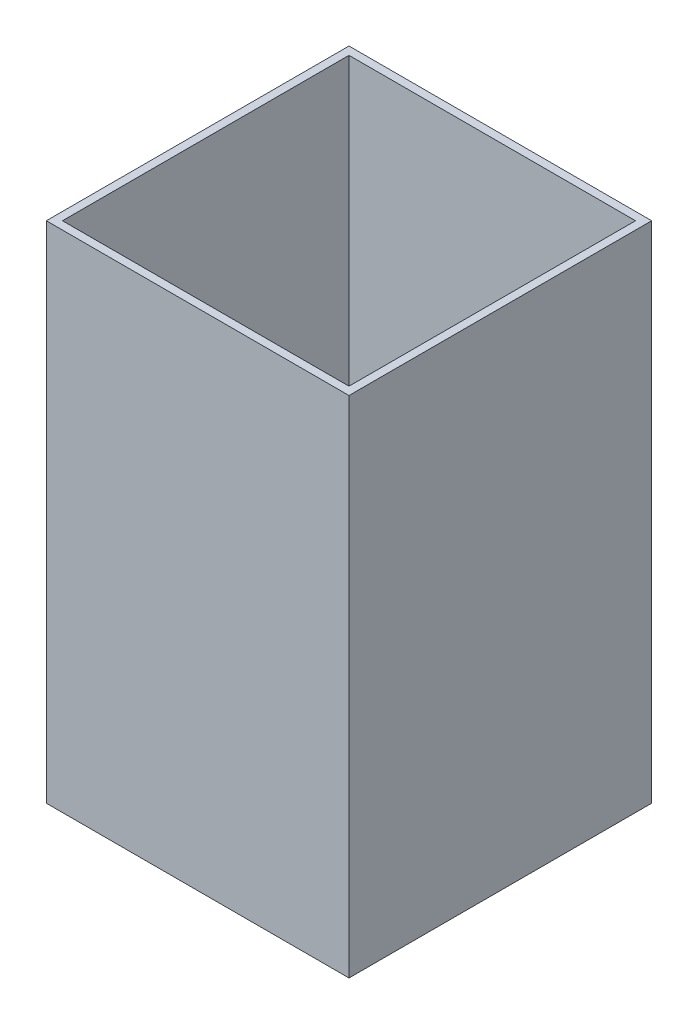
SolidWorks part; units mm, degrees
material "Corrugated Paper"
ref_plane "Front Plane" through (0, 0, 0) normal (0, 0, 1) x (1, 0, 0)
ref_plane "Top Plane" through (0, 0, 0) normal (0, 1, 0) x (1, 0, 0)
ref_plane "Right Plane" through (0, 0, 0) normal (1, 0, 0) x (0, 0, -1)
sketch "Sketch1" plane through (0, 0, 0) normal (0, 1, 0) x (1, 0, 0)
  line L0 (9.525, 19.05) -> (9.525, 18.542) construction
  line L1 (0, 0) -> (19.05, 0)
  line L2 (0, 0) -> (0, 19.05)
  line L3 (0, 19.05) -> (19.05, 19.05)
  line L4 (19.05, 0) -> (19.05, 19.05)
  line L5 (0.508, 18.542) -> (18.542, 18.542)
  line L6 (0.508, 18.542) -> (0.508, 0.508)
  line L7 (0.508, 0.508) -> (18.542, 0.508)
  line L8 (18.542, 18.542) -> (18.542, 0.508)
  line L9 (19.05, 9.525) -> (18.542, 9.525) construction
  line L10 (9.525, 0) -> (9.525, 0.508) construction
  line L11 (0, 9.525) -> (0.508, 9.525) construction
  dimension "D1" = 19.05
  dimension "D2" = 0.508
extrude "Boss-Extrude1" add sketch "Sketch1" along normal blind 31.75
